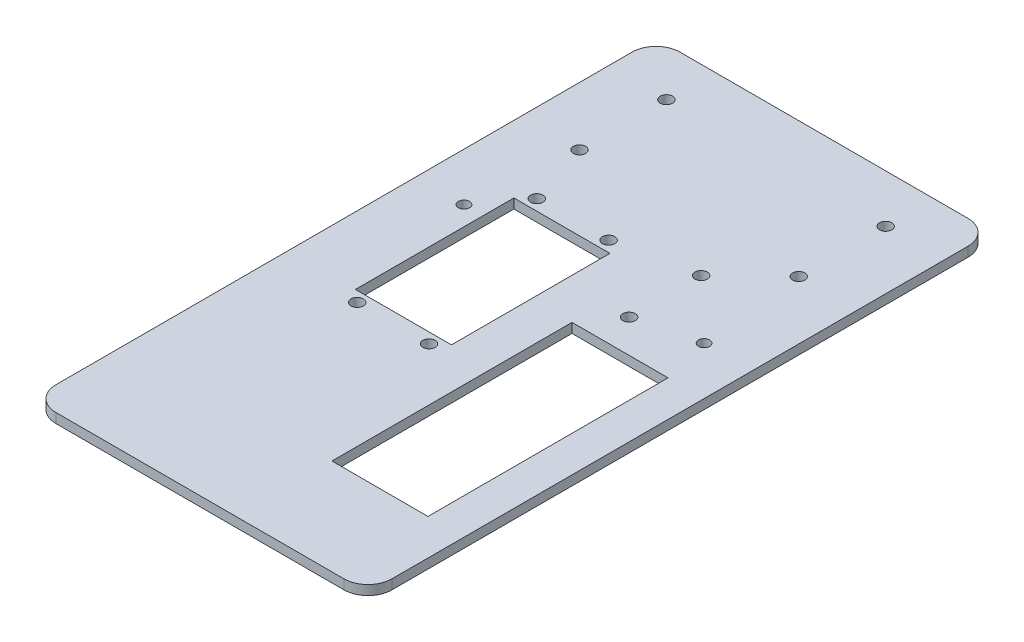
SolidWorks part; units mm, degrees
ref_plane "Front Plane" through (0, 0, 0) normal (0, 0, 1) x (1, 0, 0)
ref_plane "Top Plane" through (0, 0, 0) normal (0, 1, 0) x (1, 0, 0)
ref_plane "Right Plane" through (0, 0, 0) normal (1, 0, 0) x (0, 0, -1)
sketch "Sketch1" plane through (0, 0, 0) normal (0, 1, 0) x (1, 0, 0)
  line L0 (0, 0) -> (0, 60.5672) construction
  line L1 (-38.1, -82.55) -> (38.1, -82.55)
  line L2 (-44.45, -76.2) -> (-44.45, 76.2)
  line L3 (-38.1, 82.55) -> (38.1, 82.55)
  line L4 (44.45, -76.2) -> (44.45, 76.2)
  line L5 (-44.45, -82.55) -> (44.45, 82.55) construction
  line L6 (-44.45, 82.55) -> (44.45, -82.55) construction
  arc A0 (-38.1, -82.55) -> (-44.45, -76.2) centre (-38.1, -76.2) cw
  arc A1 (38.1, -82.55) -> (44.45, -76.2) centre (38.1, -76.2) ccw
  arc A2 (38.1, 82.55) -> (44.45, 76.2) centre (38.1, 76.2) cw
  arc A3 (-44.45, 76.2) -> (-38.1, 82.55) centre (-38.1, 76.2) cw
  circle A4 centre (-31.75, 19.05) radius 1.4732
  circle A5 centre (31.75, 19.05) radius 1.4732
  point P0 (0, 0)
  point P24 (0, 0)
  point P25 (33.2724, 38.6159)
  dimension "D3" = 6.35
  dimension "D4" = 2.9464
  dimension "D1" = 88.9
  dimension "D2" = 165.1
  dimension "D5" = 12.7
  dimension "D6" = 63.5
extrude "Boss-Extrude1" add sketch "Sketch1" along normal blind 2.54 contours A3 L2 A0 L1 A1 L4 A2 L3 A5 A4
sketch "Sketch2" plane through (0, 2.54, 0) normal (0, 1, 0) x (1, 0, 0)
  line L0 (0, 0) -> (0, 86.7977) construction
  line L1 (-29, 46.85) -> (-29, 69.85) construction
  line L2 (-29, 46.85) -> (29, 46.85) construction
  line L3 (29, 46.85) -> (29, 69.85) construction
  line L4 (-29, 69.85) -> (29, 69.85) construction
  line L5 (-38.1, 82.55) -> (38.1, 82.55) construction
  line L6 (-13.97, 30.0225) -> (-13.97, 12.7351) construction
  line L7 (-23.47, 30.0225) -> (-4.47, 30.0225) construction
  line L8 (-23.47, 30.0225) -> (-23.47, -17.4775) construction
  line L9 (-23.47, -17.4775) -> (-4.47, -17.4775) construction
  line L10 (-4.47, 30.0225) -> (-4.47, -17.4775) construction
  line L11 (-26.67, 34.15) -> (-1.27, 34.15) construction
  line L12 (-26.67, 34.15) -> (-26.67, -59.83) construction
  line L13 (-26.67, -59.83) -> (-1.27, -59.83) construction
  line L14 (-1.27, 34.15) -> (-1.27, -59.83) construction
  line L15 (15.875, 34.15) -> (15.875, 15.1) construction
  circle A1 centre (-31.75, 19.05) radius 1.4732 construction
  dimension "D1" = 23
  dimension "D2" = 58
  dimension "D3" = 12.7
  dimension "D4" = 25.4
  dimension "D5" = 19
  dimension "D6" = 47.5
  dimension "D7" = 4.1275
  dimension "D8" = 93.98
  dimension "D9" = 12.7
  dimension "D10" = 5.08
  dimension "D11" = 19.05
  dimension "D12" = 15.875
hole_wizard "#4 Clearance Hole1" positions "3DSketch1" profile "Sketch3" hole size "#4" standard "ANSI Inch" end condition up to next
sketch3d "3DSketch1"
  point P0 (-29, 2.54, -69.85)
  point P3 (29, 2.54, -69.85)
  point P6 (29, 2.54, -46.85)
  point P9 (-29, 2.54, -46.85)
  point P12 (-23.47, 2.54, -30.0225)
  point P15 (-4.47, 2.54, -30.0225)
  point P18 (-4.47, 2.54, 17.4775)
  point P21 (-23.47, 2.54, 17.4775)
  point P25 (15.875, 2.54, -34.15)
  point P28 (15.875, 2.54, -15.1)
sketch "Sketch3" plane through (-29, 2.54, -69.85) normal (1, 0, 0) x (0, 0, 1)
  line L0 (0, 0) -> (0, 2.54)
  line L1 (0, 2.54) -> (1.6319, 2.54)
  line L2 (1.6319, 2.54) -> (1.6319, 0)
  line L5 (1.6319, 0) -> (0, 0)
  line L11 (0, -6.35) -> (0, 107.95) construction
  dimension "Thru Hole Dia." = 3.2639
  dimension "Thru Hole Depth" = 2.54
sketch "Sketch4" plane through (0, 2.54, 0) normal (0, 1, 0) x (1, 0, 0)
  line L0 (-38.1, -82.55) -> (38.1, -82.55) construction
  line L1 (9.525, 6.35) -> (34.925, 6.35)
  line L2 (9.525, 6.35) -> (9.525, -57.15)
  line L3 (9.525, -57.15) -> (34.925, -57.15)
  line L4 (34.925, 6.35) -> (34.925, -57.15)
  line L5 (44.45, -76.2) -> (44.45, 76.2) construction
  line L6 (-1.27, 34.15) -> (-1.27, -59.83) construction
  line L7 (-26.67, 27.165) -> (-1.27, 27.165)
  line L8 (-26.67, 27.165) -> (-26.67, -14.745)
  line L9 (-26.67, -14.745) -> (-1.27, -14.745)
  line L10 (-1.27, 27.165) -> (-1.27, -14.745)
  line L11 (-26.67, 34.15) -> (-26.67, -59.83) construction
  line L12 (-1.27, 34.15) -> (-1.27, -59.83) construction
  line L13 (-26.67, 34.15) -> (-26.67, -59.83) construction
  line L14 (-26.67, 34.15) -> (-1.27, 34.15) construction
  dimension "D1" = 63.5
  dimension "D2" = 25.4
  dimension "D3" = 25.4
  dimension "D4" = 9.525
  dimension "D5" = 41.91
  dimension "D6" = 6.985
extrude "Cut-Extrude1" cut sketch "Sketch4" against normal up to next contours L2 L3 L4 L1 | L8 L7 L10 L9
